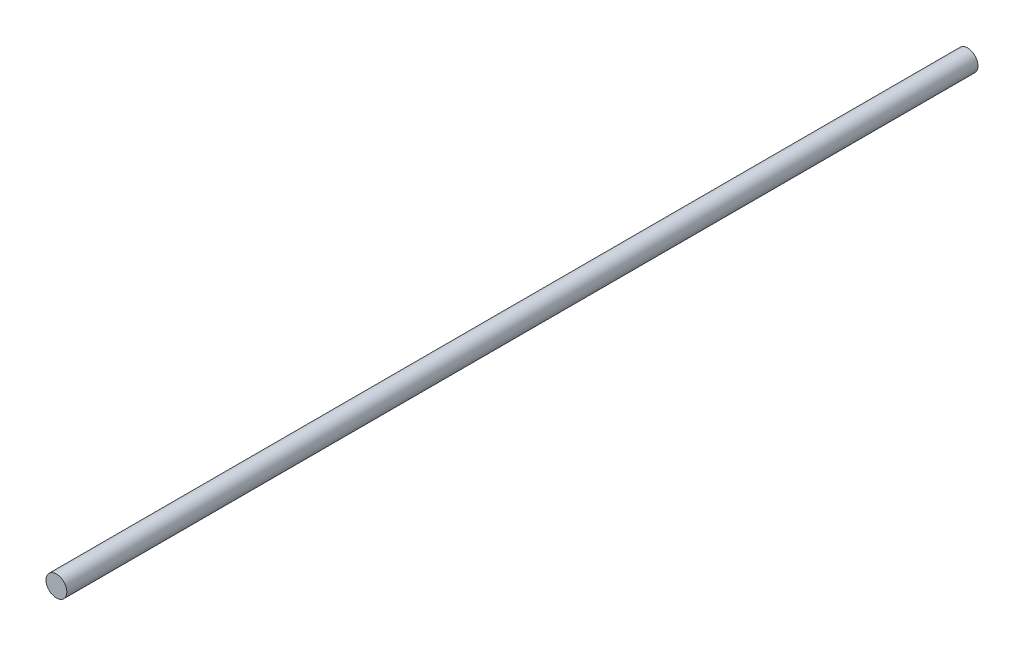
SolidWorks part; units mm, degrees
ref_plane "Přední rovina" through (0, 0, 0) normal (0, 0, 1) x (1, 0, 0)
ref_plane "Horní rovina" through (0, 0, 0) normal (0, 1, 0) x (1, 0, 0)
ref_plane "Pravá rovina" through (0, 0, 0) normal (1, 0, 0) x (0, 0, -1)
sketch "Skica1" plane through (0, 0, 0) normal (0, 0, 1) x (1, 0, 0)
  circle A0 centre (0, 0) radius 4
  dimension "D1" = 8
extrude "Přidat vysunutím1" add sketch "Skica1" along normal blind 350
